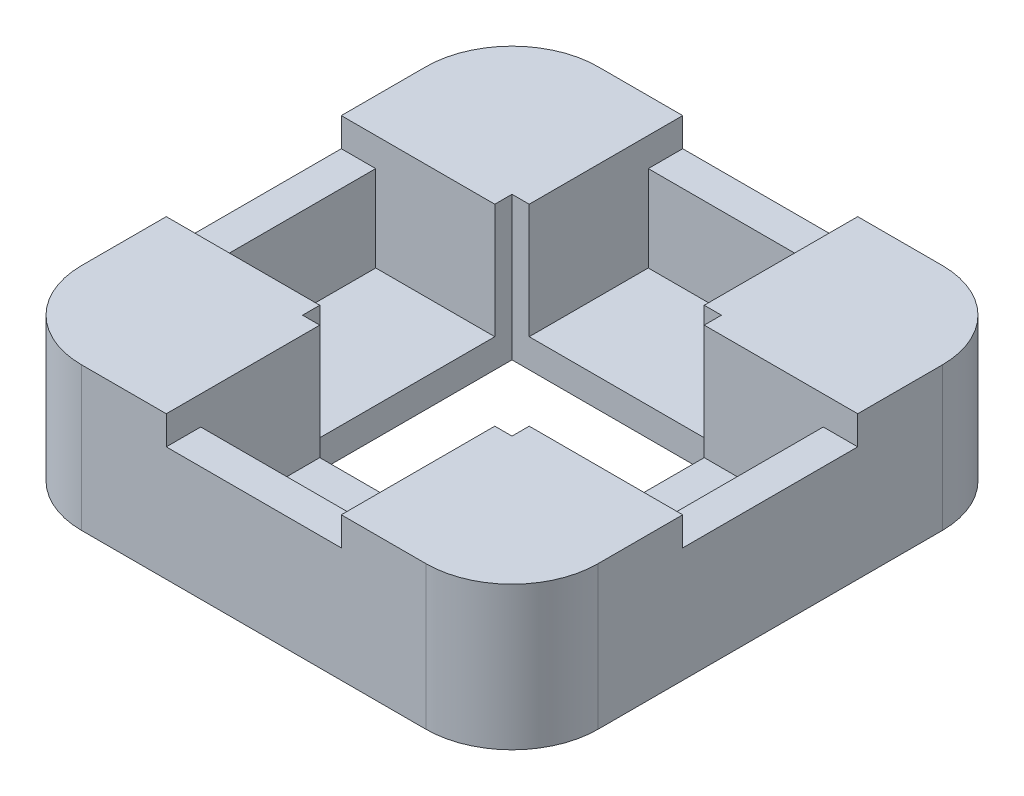
SolidWorks part; units mm, degrees
ref_plane "Front Plane" through (0, 0, 0) normal (0, 0, 1) x (1, 0, 0)
ref_plane "Top Plane" through (0, 0, 0) normal (0, 1, 0) x (1, 0, 0)
ref_plane "Right Plane" through (0, 0, 0) normal (1, 0, 0) x (0, 0, -1)
sketch "Sketch1" plane through (0, 0, 0) normal (0, 1, 0) x (1, 0, 0)
  line L0 (0, 9) -> (0, -9) construction
  line L13 (-9, 0) -> (9, 0) construction
  line L14 (-6, -9) -> (6, -9)
  line L15 (-3.65, -3.65) -> (3.65, -3.65)
  line L16 (-3.65, -3.65) -> (-3.65, 3.65)
  line L17 (-3.65, 3.65) -> (3.65, 3.65)
  line L18 (3.65, -3.65) -> (3.65, 3.65)
  line L19 (-3.65, -3.65) -> (3.65, 3.65) construction
  line L20 (-3.65, 3.65) -> (3.65, -3.65) construction
  line L21 (9, -6) -> (9, 6)
  line L22 (-6, 9) -> (6, 9)
  line L23 (-9, -6) -> (-9, 6)
  arc A0 (6, -9) -> (9, -6) centre (6, -6) ccw
  arc A1 (6, 9) -> (9, 6) centre (6, 6) cw
  arc A2 (-6, 9) -> (-9, 6) centre (-6, 6) ccw
  arc A3 (-6, -9) -> (-9, -6) centre (-6, -6) cw
  point P0 (0, 0)
  point P6 (0, 0)
  dimension "D1" = 7.3
  dimension "D2" = 18
  dimension "D3" = 6
extrude "Boss-Extrude1" add sketch "Sketch1" along normal blind 1
sketch "Sketch2" plane through (0, 1, 0) normal (0, 1, 0) x (1, 0, 0)
  line L5 (9, 9) -> (-9, -9) construction
  line L6 (8.9471, -8.9471) -> (-8.9999, 8.9999) construction
  line L18 (0, -9) -> (0, -3.65) construction
  line L20 (-3.05, -3.65) -> (-3.05, -7.8)
  line L21 (-3.05, -7.8) -> (3.05, -7.8)
  line L22 (3.05, -3.65) -> (3.05, -7.8)
  line L23 (-3.05, -3.65) -> (-3.65, -3.65)
  line L24 (3.05, -3.65) -> (3.65, -3.65)
  line L25 (-9, 0) -> (9, 0) construction
  line L26 (3.05, 3.65) -> (3.65, 3.65)
  line L27 (-3.05, 3.65) -> (-3.65, 3.65)
  line L28 (3.05, 3.65) -> (3.05, 7.8)
  line L29 (-3.05, 7.8) -> (3.05, 7.8)
  line L30 (-3.05, 3.65) -> (-3.05, 7.8)
  line L31 (3.65, -3.05) -> (7.8, -3.05)
  line L32 (7.8, -3.05) -> (7.8, 3.05)
  line L33 (3.65, 3.05) -> (7.8, 3.05)
  line L34 (3.65, -3.05) -> (3.65, -3.65)
  line L35 (3.65, 3.05) -> (3.65, 3.65)
  line L36 (-3.65, 3.05) -> (-3.65, 3.65)
  line L37 (-3.65, -3.05) -> (-3.65, -3.65)
  line L38 (-3.65, 3.05) -> (-7.8, 3.05)
  line L39 (-7.8, -3.05) -> (-7.8, 3.05)
  line L40 (-3.65, -3.05) -> (-7.8, -3.05)
  line L41 (-3.65, -3.65) -> (3.65, -3.65) construction
  line L42 (-3.05, -3.65) -> (3.05, -3.65) construction
  line L45 (-6, -9) -> (6, -9)
  line L46 (9, -6) -> (9, 6)
  line L47 (6, 9) -> (-6, 9)
  line L48 (-9, 6) -> (-9, -6)
  arc A4 (6, -9) -> (9, -6) centre (6, -6) ccw
  arc A5 (9, 6) -> (6, 9) centre (6, 6) ccw
  arc A6 (-6, 9) -> (-9, 6) centre (-6, 6) ccw
  arc A7 (-9, -6) -> (-6, -9) centre (-6, -6) ccw
  point P0 (0, 0)
  dimension "D1" = 6.1
  dimension "D2" = 15.6
extrude "Boss-Extrude2" add sketch "Sketch2" along normal blind 3
sketch "Sketch3" plane through (0, 4, 0) normal (0, 1, 0) x (1, 0, 0)
  line L0 (-3.65, -3.05) -> (-3.65, -3.65)
  line L17 (-3.65, -3.65) -> (-3.05, -3.65)
  line L18 (-3.05, -3.65) -> (-3.05, -9)
  line L22 (9, -6) -> (9, 6) construction
  line L23 (-9, -3.05) -> (-3.65, -3.05)
  line L24 (-9, 0) -> (9, 0) construction
  line L25 (-6, -9) -> (6, -9) construction
  line L26 (0, 9) -> (0, -9) construction
  line L27 (6, -9) -> (3.05, -9)
  line L46 (-9, -3.05) -> (-9, -6)
  line L47 (-6, -9) -> (-3.05, -9)
  line L48 (9, -3.05) -> (9, -6)
  line L49 (9, -3.05) -> (3.65, -3.05)
  line L50 (3.05, -3.65) -> (3.05, -9)
  line L51 (3.65, -3.65) -> (3.05, -3.65)
  line L52 (3.65, -3.05) -> (3.65, -3.65)
  line L53 (3.65, 3.05) -> (3.65, 3.65)
  line L54 (3.65, 3.65) -> (3.05, 3.65)
  line L55 (3.05, 3.65) -> (3.05, 9)
  line L56 (9, 3.05) -> (3.65, 3.05)
  line L57 (9, 3.05) -> (9, 6)
  line L58 (-6, 9) -> (-3.05, 9)
  line L59 (-9, 3.05) -> (-9, 6)
  line L60 (6, 9) -> (3.05, 9)
  line L61 (-9, 3.05) -> (-3.65, 3.05)
  line L62 (-3.05, 3.65) -> (-3.05, 9)
  line L63 (-3.65, 3.65) -> (-3.05, 3.65)
  line L64 (-3.65, 3.05) -> (-3.65, 3.65)
  arc A0 (-9, -6) -> (-6, -9) centre (-6, -6) ccw
  arc A1 (9, -6) -> (6, -9) centre (6, -6) cw
  arc A2 (9, 6) -> (6, 9) centre (6, 6) ccw
  arc A3 (-9, 6) -> (-6, 9) centre (-6, 6) cw
extrude "Boss-Extrude3" add sketch "Sketch3" along normal blind 1
